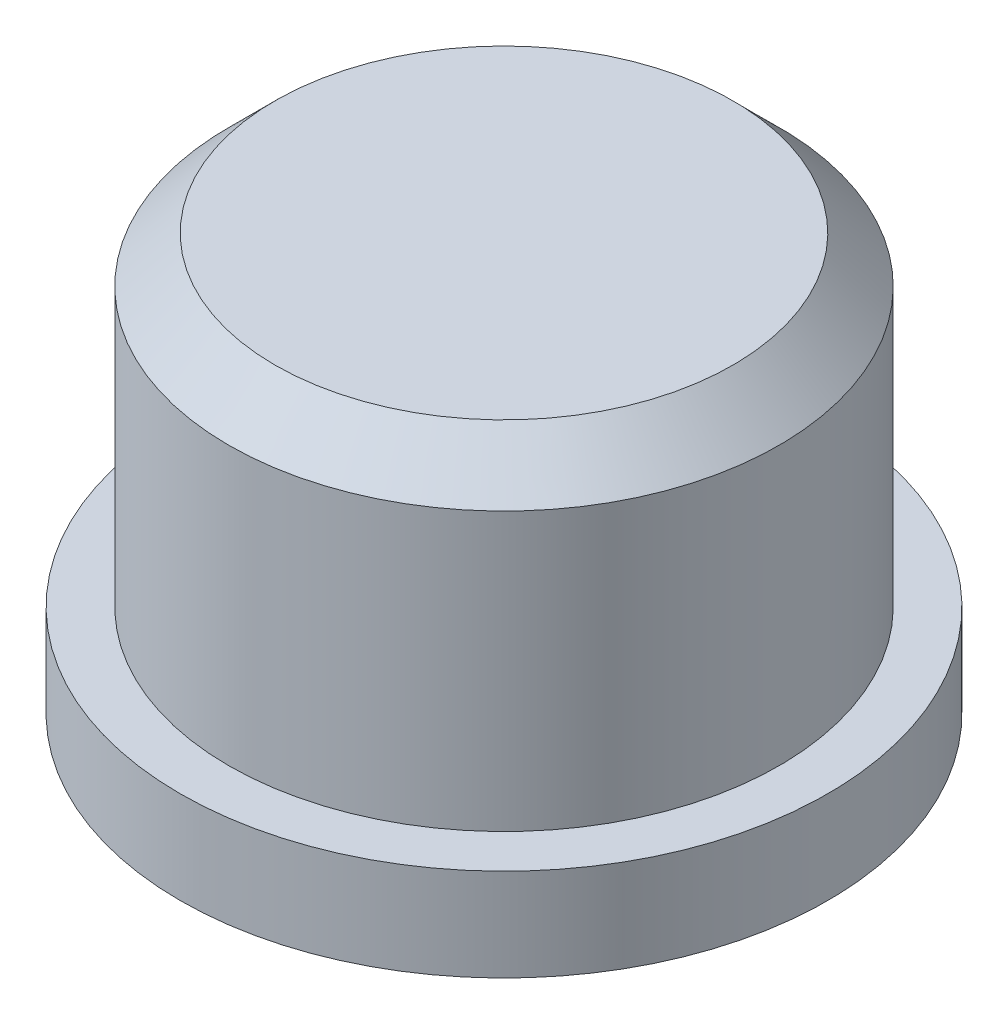
SolidWorks part; units mm, degrees
ref_plane "Front Plane" through (0, 0, 0) normal (0, 0, 1) x (1, 0, 0)
ref_plane "Top Plane" through (0, 0, 0) normal (0, 1, 0) x (1, 0, 0)
ref_plane "Right Plane" through (0, 0, 0) normal (1, 0, 0) x (0, 0, -1)
sketch "Sketch1" plane through (0, 0, 0) normal (0, 1, 0) x (1, 0, 0)
  circle A0 centre (0, 0) radius 7
  dimension "D1" = 14
extrude "Boss-Extrude1" add sketch "Sketch1" along normal blind 2
sketch "Sketch2" plane through (0, 2, 0) normal (0, 1, 0) x (1, 0, 0)
  circle A0 centre (0, 0) radius 5.95
  dimension "D1" = 11.9
extrude "Boss-Extrude2" add sketch "Sketch2" along normal blind 7
sketch "Sketch3" plane through (0, 0, 0) normal (0, -1, 0) x (1, 0, 0)
  line L1 (-1.9, -1.9) -> (1.9, -1.9)
  line L2 (-1.9, -1.9) -> (-1.9, 1.9)
  line L3 (-1.9, 1.9) -> (1.9, 1.9)
  line L4 (1.9, -1.9) -> (1.9, 1.9)
  line L5 (-1.9, -1.9) -> (1.9, 1.9) construction
  line L6 (-1.9, 1.9) -> (1.9, -1.9) construction
  circle A0 centre (0, 0) radius 2.687
  dimension "D1" = 3.8
  dimension "D2" = 3.8
extrude "Cut-Extrude1" cut sketch "Sketch3" against normal blind 1.8 contours L2 A0 | L1 L4 L3 L2 | L3 A0 | L4 A0 | L1 A0
chamfer "Chamfer1" distance 1 angle 45 1 edges at (0, 9, 5.95)
